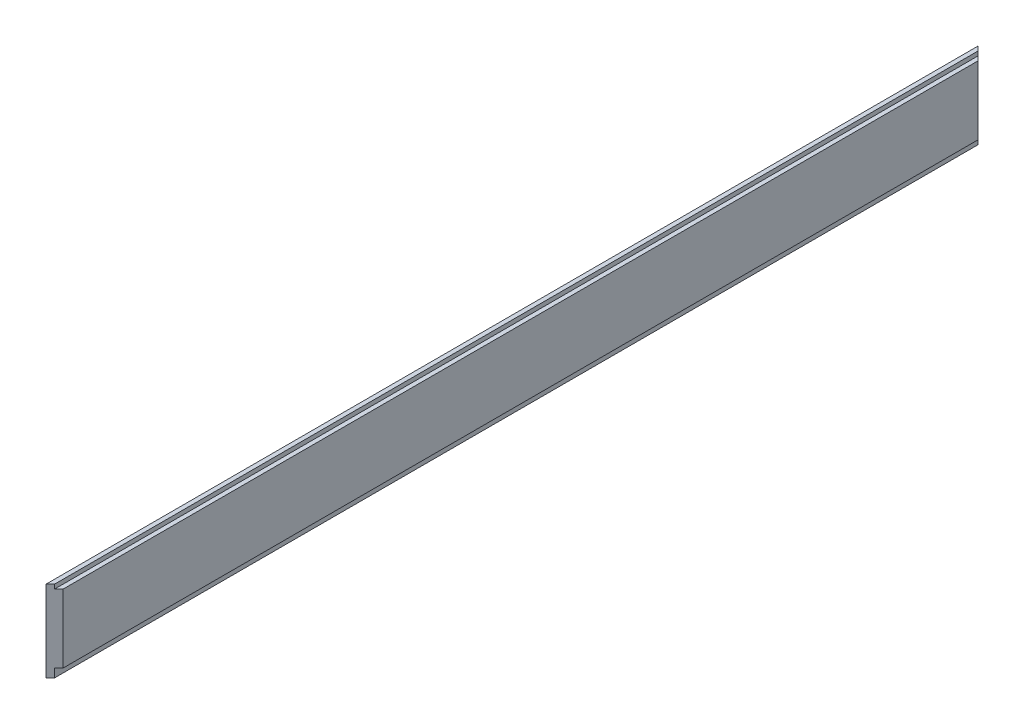
SolidWorks part; units mm, degrees
material "Pine"
ref_plane "Front Plane" through (0, 0, 0) normal (0, 0, 1) x (1, 0, 0)
ref_plane "Top Plane" through (0, 0, 0) normal (0, 1, 0) x (1, 0, 0)
ref_plane "Right Plane" through (0, 0, 0) normal (1, 0, 0) x (0, 0, -1)
sketch "Sketch1" plane through (0, 0, 0) normal (0, 0, 1) x (1, 0, 0)
  line L0 (0, 0) -> (0, 60.325)
  line L1 (0, 60.325) -> (3.175, 60.325)
  line L2 (3.175, 60.325) -> (3.175, 57.15)
  line L3 (3.175, 57.15) -> (6.35, 57.15)
  line L4 (6.35, 57.15) -> (6.35, 6.35)
  line L5 (6.35, 6.35) -> (3.175, 6.35)
  line L6 (3.175, 6.35) -> (3.175, 0)
  line L7 (3.175, 0) -> (0, 0)
  dimension "D1" = 6.35
  dimension ".125" = 3.175
  dimension "D2" = 3.175
  dimension "D3" = 3.175
  dimension "D4" = 3.175
  dimension "D5" = 50.8
extrude "Boss-Extrude1" add sketch "Sketch1" along normal blind 692.15 contours L0 L1 L2 L3 L4 L5 L6 L7
sketch "Sketch2" plane through (0, 60.325, 0) normal (0, 1, 0) x (1, 0, 0)
  line L4 (0, 0) -> (6.35, -6.35)
  line L5 (6.35, -692.15) -> (6.35, 0) construction
  line L6 (0, 0) -> (6.35, 0)
  line L7 (6.35, 0) -> (6.35, -6.35)
  dimension "D1" = 6.35
extrude "Cut-Extrude1" cut sketch "Sketch2" against normal through all
ref_plane "Plane1" through (0, 0, 346.075) normal (0, 0, 1) x (1, 0, 0)
mirror "Mirror1" about plane through (0, 0, 346.075) normal (0, 0, 1) of "Cut-Extrude1"
